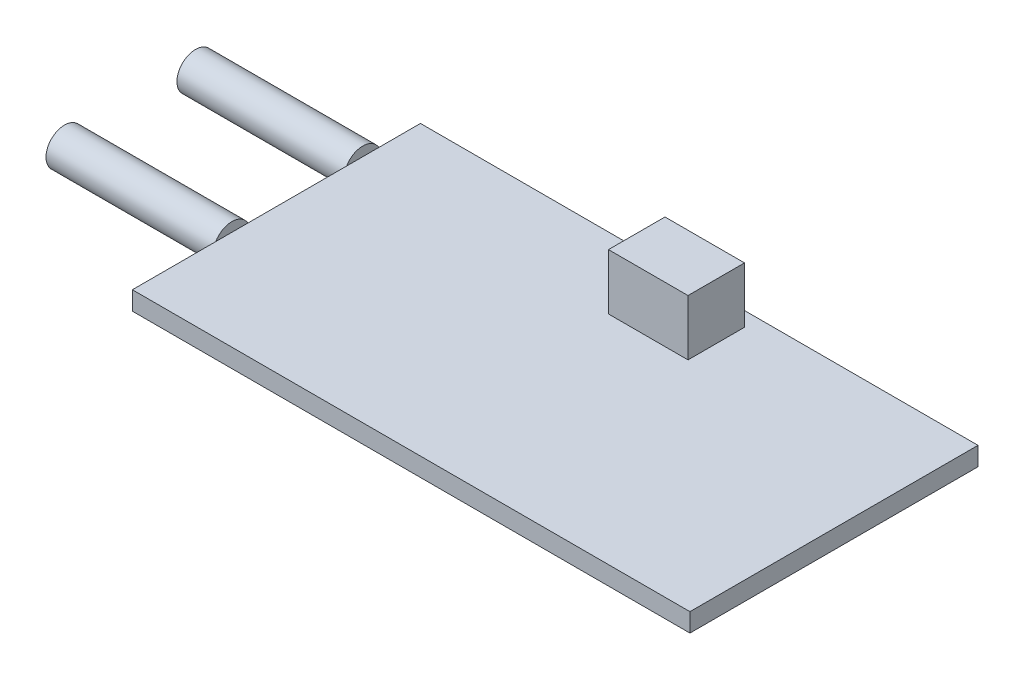
SolidWorks part; units mm, degrees
ref_plane "Front Plane" through (0, 0, 0) normal (0, 0, 1) x (1, 0, 0)
ref_plane "Top Plane" through (0, 0, 0) normal (0, 1, 0) x (1, 0, 0)
ref_plane "Right Plane" through (0, 0, 0) normal (1, 0, 0) x (0, 0, -1)
sketch "Sketch1" plane through (0, 0, 0) normal (0, 1, 0) x (1, 0, 0)
  line L1 (-13.2566, 3.8213) -> (16.7434, 3.8213)
  line L2 (-13.2566, 3.8213) -> (-13.2566, -11.6787)
  line L3 (-13.2566, -11.6787) -> (16.7434, -11.6787)
  line L4 (16.7434, 3.8213) -> (16.7434, -11.6787)
  dimension "D1" = 30
  dimension "D2" = 15.5
extrude "Boss-Extrude1" add sketch "Sketch1" along normal blind 1
sketch "Sketch2" plane through (-13.2566, 0, 0) normal (-1, 0, 0) x (0, 0, 1)
  circle A0 centre (-0.7178, 0.5) radius 1
  circle A1 centre (6.3265, 0.5) radius 1
extrude "Boss-Extrude2" add sketch "Sketch2" along normal blind 9
sketch "Sketch3" plane through (0, 1, 0) normal (0, 1, 0) x (1, 0, 0)
  line L1 (0.6817, 3.0408) -> (4.9611, 3.0408)
  line L2 (0.6817, 3.0408) -> (0.6817, 0)
  line L3 (0.6817, 0) -> (4.9611, 0)
  line L4 (4.9611, 3.0408) -> (4.9611, 0)
extrude "Boss-Extrude3" add sketch "Sketch3" along normal blind 3
